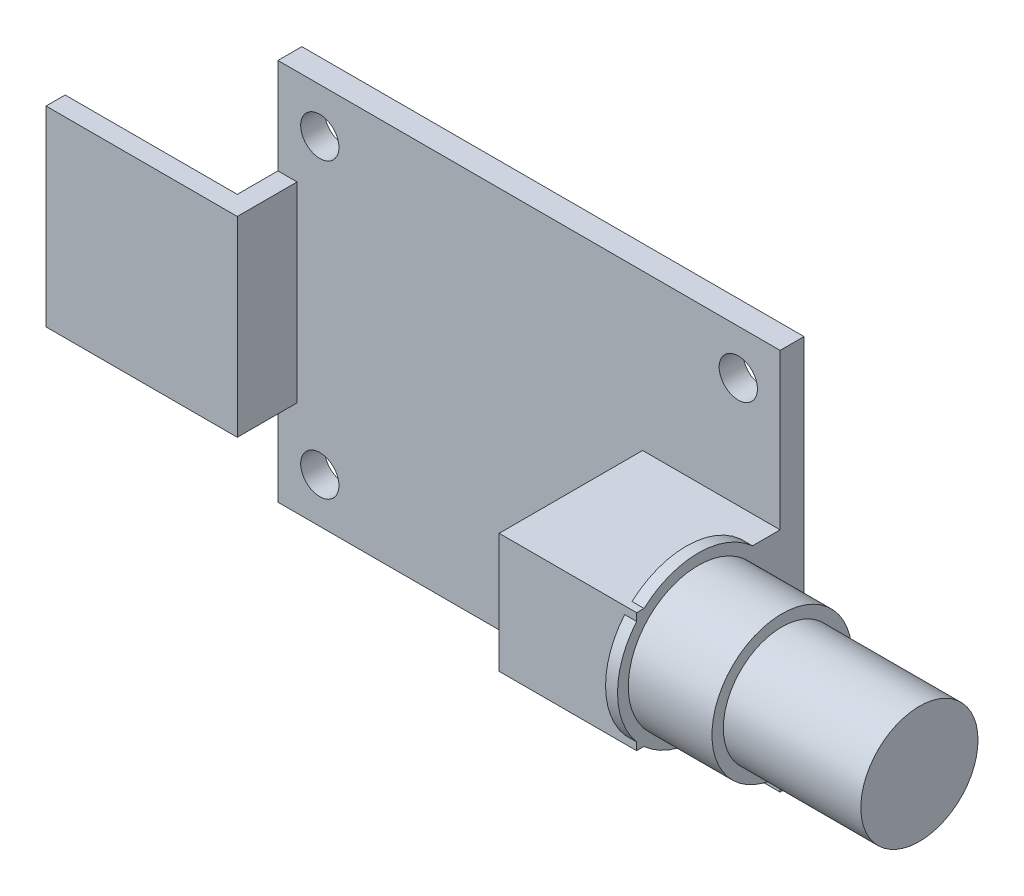
SolidWorks part; units mm, degrees
ref_plane "Alzado" through (0, 0, 0) normal (0, 0, 1) x (1, 0, 0)
ref_plane "Planta" through (0, 0, 0) normal (0, 1, 0) x (1, 0, 0)
ref_plane "Vista lateral" through (0, 0, 0) normal (1, 0, 0) x (0, 0, -1)
sketch "Croquis1" plane through (0, 0, 0) normal (0, 0, 1) x (1, 0, 0)
  line L1 (-21, 16) -> (21, 16)
  line L2 (-21, 16) -> (-21, -16)
  line L3 (-21, -16) -> (21, -16)
  line L4 (21, 16) -> (21, -16)
  line L5 (-21, 16) -> (21, -16) construction
  line L6 (-21, -16) -> (21, 16) construction
  line L7 (17.5, 12.25) -> (-17.5, 12.25) construction
  line L8 (17.5, 12.25) -> (17.5, -12.25) construction
  line L9 (17.5, -12.25) -> (-17.5, -12.25) construction
  line L10 (-17.5, 12.25) -> (-17.5, -12.25) construction
  line L11 (0, -12.25) -> (0, 12.25) construction
  line L12 (17.5, 0) -> (-17.5, 0) construction
  circle A0 centre (-17.5, 12.25) radius 1.6
  circle A1 centre (-17.5, -12.25) radius 1.6
  circle A2 centre (17.5, -12.25) radius 1.6
  circle A3 centre (17.5, 12.25) radius 1.6
  point P0 (0, 0)
  point P5 (0, 0)
  dimension "D5" = 3.2
  dimension "D1" = 32
  dimension "D2" = 42
  dimension "D3" = 24.5
  dimension "D4" = 35
extrude "Saliente-Extruir1" add sketch "Croquis1" along normal blind 2
sketch "Croquis2" plane through (0, 0, 2) normal (0, 0, 1) x (1, 0, 0)
  line L0 (21, -16) -> (21, 16) construction
  line L1 (21, -7) -> (9.5, -7)
  line L2 (21, -7) -> (21, 3)
  line L3 (21, 3) -> (9.5, 3)
  line L4 (9.5, -7) -> (9.5, 3)
  line L5 (21, 16) -> (-21, 16) construction
  line L6 (-21, -16) -> (21, -16) construction
  dimension "D1" = 10
  dimension "D2" = 11.5
  dimension "D3" = 23
  dimension "D4" = 19
extrude "Saliente-Extruir2" add sketch "Croquis2" along normal blind 12
sketch "Croquis3" plane through (21, 0, 0) normal (1, 0, 0) x (0, 0, -1)
  line L0 (-14, -2) -> (-15.6, -2) construction
  line L1 (-14, -7) -> (-14, 3) construction
  circle A0 centre (-8.85, -2) radius 6.75
  dimension "D1" = 1.6
  dimension "D2" = 13.5
extrude "Saliente-Extruir3" add sketch "Croquis3" along normal blind 19.5 from offset 1 offset against normal yes
sketch "Croquis4" plane through (39.5, 0, 0) normal (1, 0, 0) x (0, 0, -1)
  circle A0 centre (-8.85, -2) radius 5.85
  circle A1 centre (-8.85, -2) radius 6.75 construction
  circle A2 centre (-8.85, -2) radius 6.75
  dimension "D1" = 11.7
extrude "Cortar-Extruir1" cut sketch "Croquis4" against normal offset from surface (18.5 mm away) 1 up to face at (20, 3.875, 8.85)
sketch "Croquis5" plane through (39.5, 0, 0) normal (1, 0, 0) x (0, 0, -1)
  circle A0 centre (-8.85, -2) radius 4.9
  circle A1 centre (-8.85, -2) radius 5.85 construction
  circle A2 centre (-8.85, -2) radius 5.85
  dimension "D1" = 9.8
extrude "Cortar-Extruir2" cut sketch "Croquis5" against normal offset from surface (11.5 mm away) 7 up to face at (21, -1.4286, 7.2143)
sketch "Croquis7" plane through (0, 0, 0) normal (0, 1, 0) x (1, 0, 0)
  line L0 (-21, -2) -> (-21, -5.4)
  line L1 (-21, -5.4) -> (-35.4, -5.4)
  line L2 (-35.4, -5.4) -> (-35.4, -7)
  line L3 (-35.4, -7) -> (-19.4, -7)
  line L4 (-19.4, -7) -> (-19.4, -2)
  line L5 (-21, -2) -> (21, -2) construction
  line L6 (-19.4, -2) -> (-21, -2)
  dimension "D1" = 1.6
  dimension "D2" = 16
  dimension "D3" = 5
extrude "Saliente-Extruir4" add sketch "Croquis7" along normal mid plane 16
